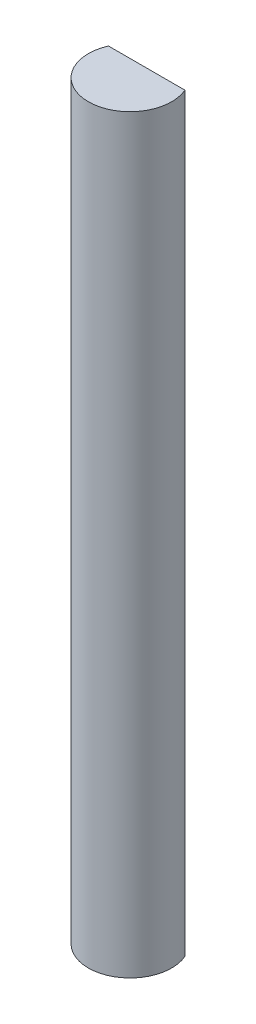
SolidWorks part; units mm, degrees
ref_plane "Front Plane" through (0, 0, 0) normal (0, 0, 1) x (1, 0, 0)
ref_plane "Top Plane" through (0, 0, 0) normal (0, 1, 0) x (1, 0, 0)
ref_plane "Right Plane" through (0, 0, 0) normal (1, 0, 0) x (0, 0, -1)
sketch "Sketch2" plane through (0, 0, 0) normal (0, 1, 0) x (1, 0, 0)
  line L0 (-9.1652, 4) -> (9.1652, 4)
  arc A0 (-9.1652, 4) -> (9.1652, 4) centre (0, 0) ccw
  dimension "D1" = 20
  dimension "D2" = 4
extrude "Boss-Extrude1" add sketch "Sketch2" along normal blind 180
sketch "Sketch3" plane through (0, 0, -4) normal (0, 0, -1) x (-1, 0, 0)
  line L0 (-9.1652, 180) -> (9.1652, 180) construction
  line L1 (-7.0776, 170.6) -> (6.9224, 170.6)
  line L2 (-7.0776, 170.6) -> (-7.0776, 177)
  line L3 (-7.0776, 177) -> (6.9224, 177)
  line L4 (6.9224, 170.6) -> (6.9224, 177)
  line L5 (-7.0776, 170.6) -> (6.9224, 177) construction
  line L6 (-7.0776, 177) -> (6.9224, 170.6) construction
  line L7 (-7.0776, 160.6) -> (-7.0776, 167)
  line L8 (-7.0776, 160.6) -> (6.9224, 160.6)
  line L9 (6.9224, 160.6) -> (6.9224, 167)
  line L10 (-7.0776, 167) -> (6.9224, 167)
  line L11 (-7.0776, 150.6) -> (-7.0776, 157)
  line L12 (-7.0776, 150.6) -> (6.9224, 150.6)
  line L13 (6.9224, 150.6) -> (6.9224, 157)
  line L14 (-7.0776, 157) -> (6.9224, 157)
  line L15 (-7.0776, 140.6) -> (-7.0776, 147)
  line L16 (-7.0776, 140.6) -> (6.9224, 140.6)
  line L17 (6.9224, 140.6) -> (6.9224, 147)
  line L18 (-7.0776, 147) -> (6.9224, 147)
  line L19 (-7.0776, 130.6) -> (-7.0776, 137)
  line L20 (-7.0776, 130.6) -> (6.9224, 130.6)
  line L21 (6.9224, 130.6) -> (6.9224, 137)
  line L22 (-7.0776, 137) -> (6.9224, 137)
  line L23 (-7.0776, 120.6) -> (-7.0776, 127)
  line L24 (-7.0776, 120.6) -> (6.9224, 120.6)
  line L25 (6.9224, 120.6) -> (6.9224, 127)
  line L26 (-7.0776, 127) -> (6.9224, 127)
  line L27 (-7.0776, 110.6) -> (-7.0776, 117)
  line L28 (-7.0776, 110.6) -> (6.9224, 110.6)
  line L29 (6.9224, 110.6) -> (6.9224, 117)
  line L30 (-7.0776, 117) -> (6.9224, 117)
  line L31 (-7.0776, 100.6) -> (-7.0776, 107)
  line L32 (-7.0776, 100.6) -> (6.9224, 100.6)
  line L33 (6.9224, 100.6) -> (6.9224, 107)
  line L34 (-7.0776, 107) -> (6.9224, 107)
  line L35 (-7.0776, 90.6) -> (-7.0776, 97)
  line L36 (-7.0776, 90.6) -> (6.9224, 90.6)
  line L37 (6.9224, 90.6) -> (6.9224, 97)
  line L38 (-7.0776, 97) -> (6.9224, 97)
  line L39 (-7.0776, 80.6) -> (-7.0776, 87)
  line L40 (-7.0776, 80.6) -> (6.9224, 80.6)
  line L41 (6.9224, 80.6) -> (6.9224, 87)
  line L42 (-7.0776, 87) -> (6.9224, 87)
  line L43 (-7.0776, 70.6) -> (-7.0776, 77)
  line L44 (-7.0776, 70.6) -> (6.9224, 70.6)
  line L45 (6.9224, 70.6) -> (6.9224, 77)
  line L46 (-7.0776, 77) -> (6.9224, 77)
  line L47 (-7.0776, 60.6) -> (-7.0776, 67)
  line L48 (-7.0776, 60.6) -> (6.9224, 60.6)
  line L49 (6.9224, 60.6) -> (6.9224, 67)
  line L50 (-7.0776, 67) -> (6.9224, 67)
  line L51 (-7.0776, 50.6) -> (-7.0776, 57)
  line L52 (-7.0776, 50.6) -> (6.9224, 50.6)
  line L53 (6.9224, 50.6) -> (6.9224, 57)
  line L54 (-7.0776, 57) -> (6.9224, 57)
  line L55 (-7.0776, 40.6) -> (-7.0776, 47)
  line L56 (-7.0776, 40.6) -> (6.9224, 40.6)
  line L57 (6.9224, 40.6) -> (6.9224, 47)
  line L58 (-7.0776, 47) -> (6.9224, 47)
  point P0 (-0.0776, 173.8)
  dimension "D1" = 14
  dimension "D2" = 6.4
  dimension "D3" = 3
  dimension "D4" = 14
extrude "Cut-Extrude1" cut sketch "Sketch3" against normal blind 7
